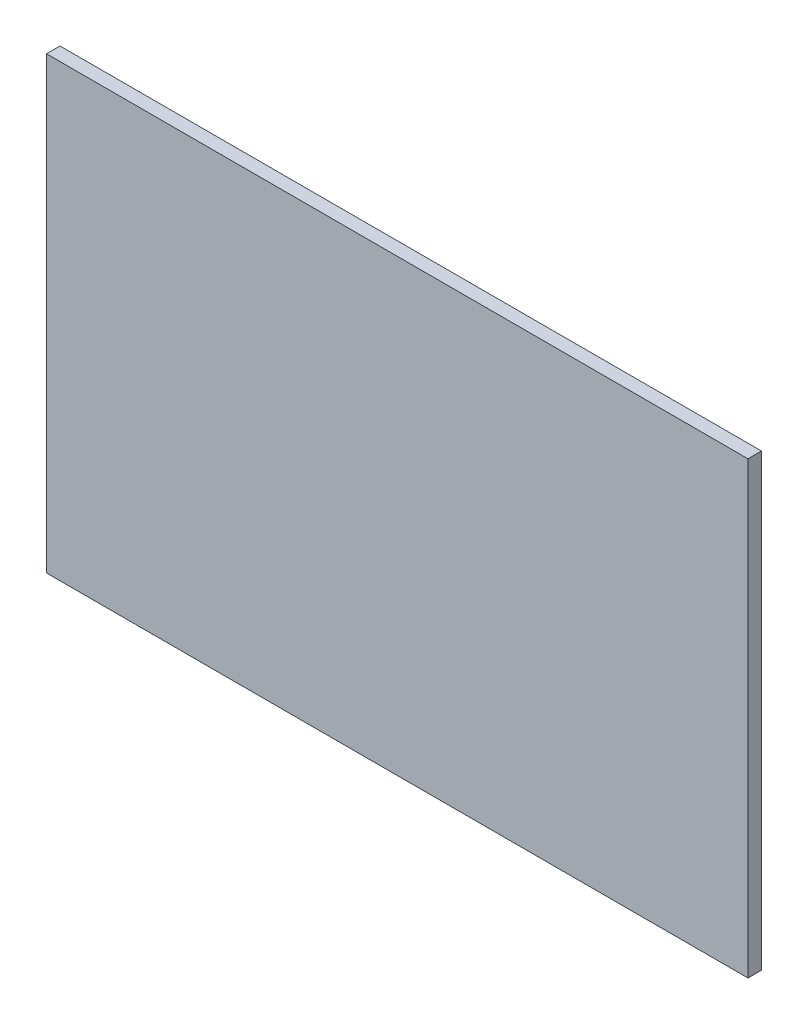
SolidWorks part; units mm, degrees
ref_plane "Plan de face" through (0, 0, 0) normal (0, 0, 1) x (1, 0, 0)
ref_plane "Plan de dessus" through (0, 0, 0) normal (0, 1, 0) x (1, 0, 0)
ref_plane "Plan de droite" through (0, 0, 0) normal (1, 0, 0) x (0, 0, -1)
sketch "Esquisse1" plane through (0, 0, 0) normal (0, 0, 1) x (1, 0, 0)
  line L1 (-78, -50) -> (78, -50)
  line L2 (-78, -50) -> (-78, 50)
  line L3 (-78, 50) -> (78, 50)
  line L4 (78, -50) -> (78, 50)
  point P0 (0, 0)
  dimension "D1" = 156
  dimension "D2" = 100
extrude "Boss.-Extru.1" add sketch "Esquisse1" along normal blind 3
